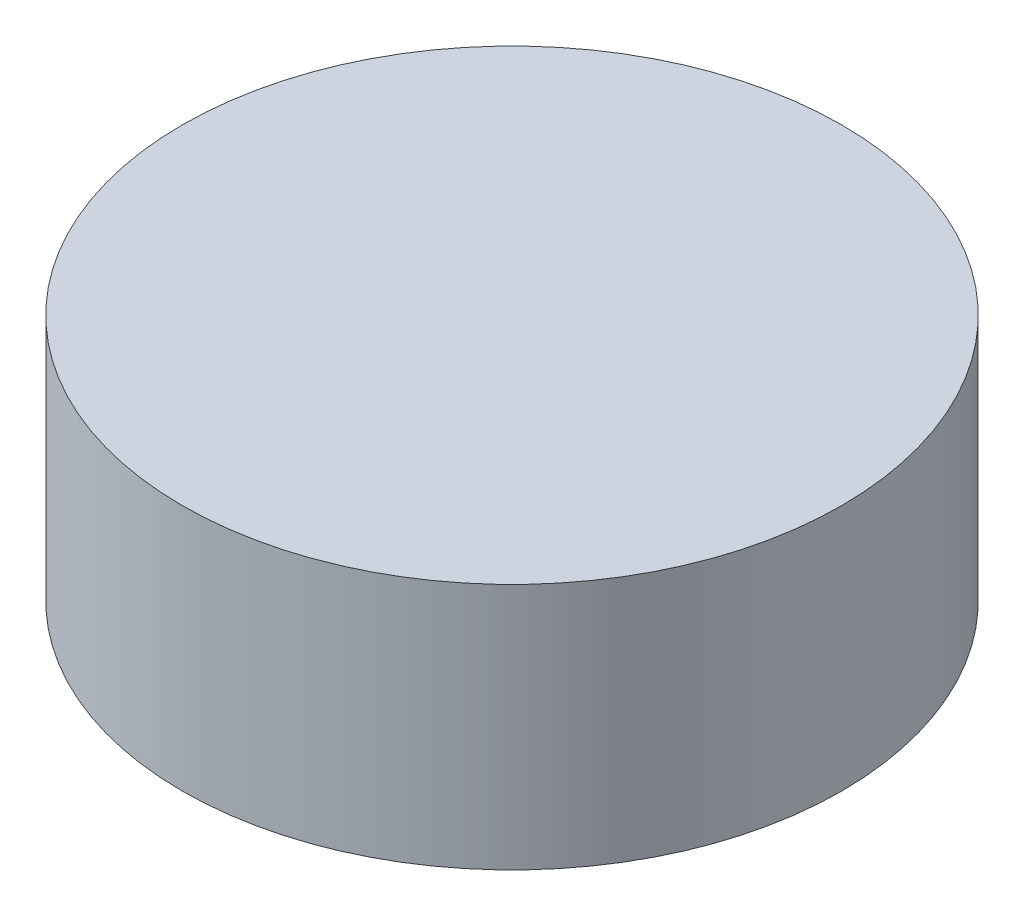
SolidWorks part; units mm, degrees
ref_plane "Front Plane" through (0, 0, 0) normal (0, 0, 1) x (1, 0, 0)
ref_plane "Top Plane" through (0, 0, 0) normal (0, 1, 0) x (1, 0, 0)
ref_plane "Right Plane" through (0, 0, 0) normal (1, 0, 0) x (0, 0, -1)
sketch "Sketch1" plane through (0, -270, 0) normal (0, -1, 0) x (1, 0, 0)
  line L0 (0, 914.6526) -> (0, 1209.2381) construction
  line L1 (-216.4624, 914.6526) -> (216.4624, 914.6526) construction
  circle A0 centre (-70, 999.1895) radius 40
  circle A1 centre (-70, 999.1895) radius 34
  dimension "D1" = 70
  dimension "D2" = 80
  dimension "D3" = 6
extrude "Boss-Extrude1" add sketch "Sketch1" along normal blind 30
ref_point "Point1"
ref_plane "Plane1" through (0, 0, 999.1895) normal (0, 0, 1) x (1, 0, 0)
sketch "Sketch3" plane through (0, 0, 999.1895) normal (0, 0, 1) x (1, 0, 0)
  line L0 (-70, -270) -> (-70, -310.6817) construction
  line L1 (-36, -270) -> (-104, -270) construction
  line L2 (-70, -304) -> (-122.7353, -304) construction
  line L3 (-110, -300) -> (-30, -300) construction
  line L4 (-110, -270) -> (-110, -300) construction
  line L5 (-104, -298.6191) -> (-104, -270)
  line L6 (-104, -270) -> (-70, -270)
  line L7 (-70, -270) -> (-70, -304)
  arc A0 (-70, -304) -> (-104, -298.6191) centre (-70, -193.8927) cw
  point P12 (-104, -298.6191)
  dimension "D2" = 6
  dimension "D1" = 4
revolve "Revolve1" add sketch "Sketch3" angle 360 about L7
